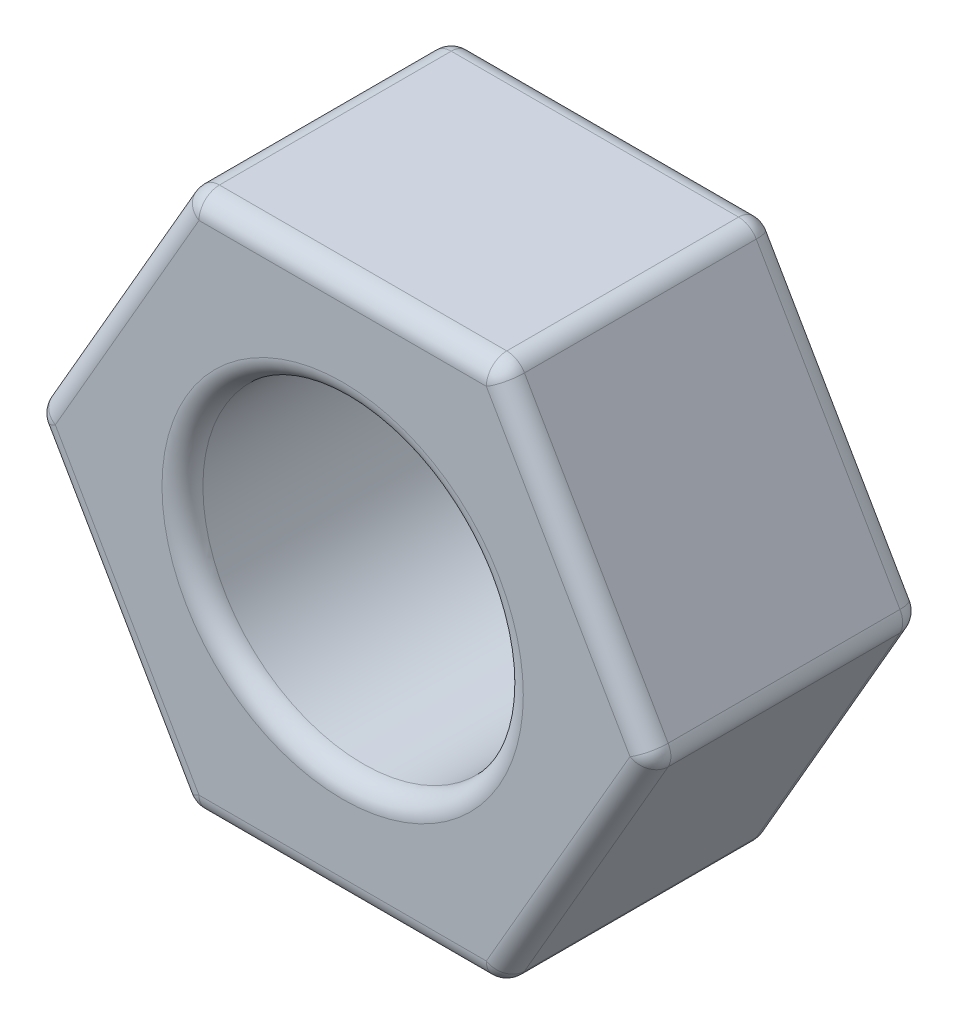
SolidWorks part; units mm, degrees
ref_plane "Plano frontal" through (0, 0, 0) normal (0, 0, 1) x (1, 0, 0)
ref_plane "Plano superior" through (0, 0, 0) normal (0, 1, 0) x (1, 0, 0)
ref_plane "Plano direito" through (0, 0, 0) normal (1, 0, 0) x (0, 0, -1)
sketch "Esboço1" plane through (0, 0, 0) normal (0, 0, 1) x (1, 0, 0)
  line L7 (-4.5611, 0) -> (-2.2805, -3.95)
  line L8 (-2.2805, -3.95) -> (2.2805, -3.95)
  line L9 (2.2805, -3.95) -> (4.5611, 0)
  line L10 (4.5611, 0) -> (2.2805, 3.95)
  line L11 (2.2805, 3.95) -> (-2.2805, 3.95)
  line L12 (-2.2805, 3.95) -> (-4.5611, 0)
  circle A0 centre (0, 0) radius 2.35
  circle A1 centre (0, 0) radius 3.95 construction
  dimension "D1" = 4.7
  dimension "D2" = 7.9
extrude "Ressalto-extrusão4" add sketch "Esboço1" along normal blind 4
fillet "Filete2" radius 0.3 20 edges at (2.35, 0, 0) (-3.4208, 1.975, 0) (-4.5611, 0, 2) (-3.4208, -1.975, 0) (-2.2805, -3.95, 2) (0, -3.95, 0) (2.2805, -3.95, 2) (3.4208, -1.975, 0) (4.5611, 0, 2) (3.4208, 1.975, 0) (2.2805, 3.95, 2) (-2.2805, 3.95, 2) (0, 3.95, 0) (2.35, 0, 4) (0, 3.95, 4) (3.4208, 1.975, 4) (3.4208, -1.975, 4) (0, -3.95, 4) (-3.4208, -1.975, 4) (-3.4208, 1.975, 4)
